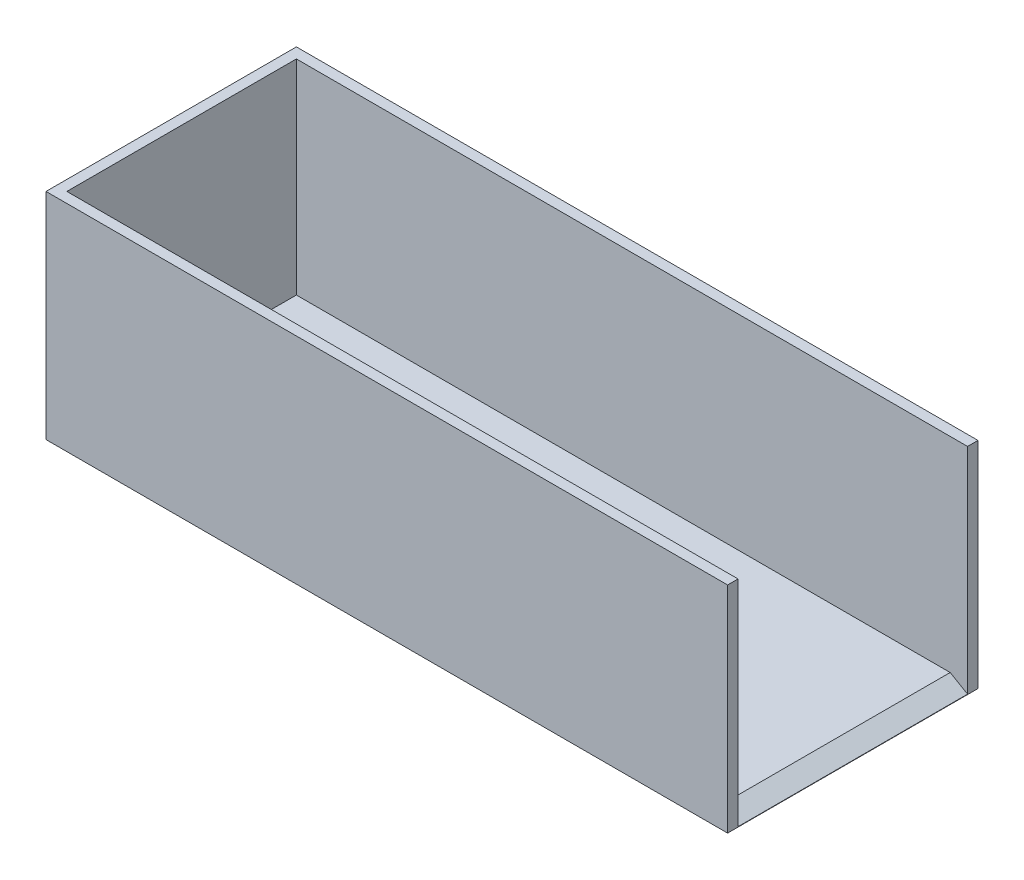
SolidWorks part; units mm, degrees
ref_plane "Plan de face" through (0, 0, 0) normal (0, 0, 1) x (1, 0, 0)
ref_plane "Plan de dessus" through (0, 0, 0) normal (0, 1, 0) x (1, 0, 0)
ref_plane "Plan de droite" through (0, 0, 0) normal (1, 0, 0) x (0, 0, -1)
sketch "Esquisse1" plane through (0, 0, 0) normal (0, 1, 0) x (1, 0, 0)
  line L1 (-37.1868, 18.9703) -> (158.8132, 18.9703)
  line L2 (-37.1868, 18.9703) -> (-37.1868, -53.0297)
  line L3 (-37.1868, -53.0297) -> (158.8132, -53.0297)
  line L4 (158.8132, 18.9703) -> (158.8132, -53.0297)
  dimension "D1" = 196
  dimension "D2" = 72
extrude "Boss.-Extru.1" add sketch "Esquisse1" along normal blind 3 contours L1 L4 L3 L2
sketch "Esquisse2" plane through (0, 3, 0) normal (0, 1, 0) x (1, 0, 0)
  line L0 (-37.1868, 18.9703) -> (158.8132, 18.9703)
  line L1 (158.8132, 18.9703) -> (158.8132, 15.9703)
  line L2 (158.8132, 15.9703) -> (-34.1868, 15.9703)
  line L3 (-34.1868, 15.9703) -> (-34.1868, -50.0297)
  line L4 (-34.1868, -50.0297) -> (158.8132, -50.0297)
  line L5 (-37.1868, 18.9703) -> (-37.1868, -53.0297)
  line L6 (-37.1868, -53.0297) -> (158.8132, -53.0297)
  line L7 (158.8132, -53.0297) -> (158.8132, -50.0297)
  dimension "D1" = 3
  dimension "D2" = 3
  dimension "D3" = 3
  dimension "D4" = 196
  dimension "D5" = 196
extrude "Boss.-Extru.2" add sketch "Esquisse2" along normal blind 58.8
chamfer "Chanfrein1" distance 5 angle 30 1 edges
